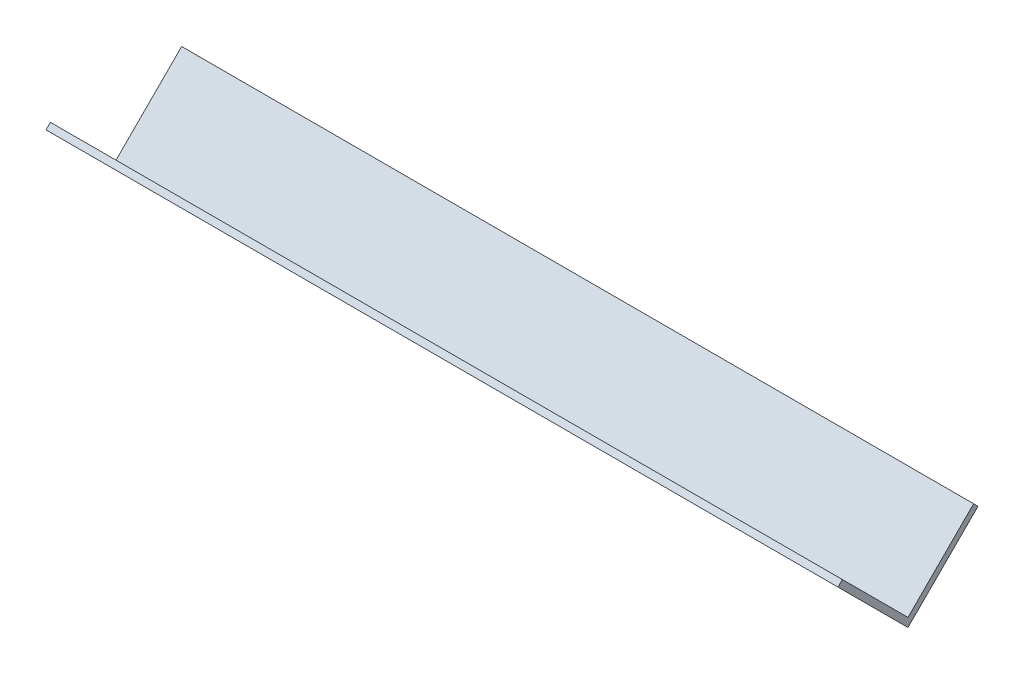
SolidWorks part; units mm, degrees
ref_plane "Front Plane" through (0, 0, 0) normal (0, 0, 1) x (1, 0, 0)
ref_plane "Top Plane" through (0, 0, 0) normal (0, 1, 0) x (1, 0, 0)
ref_plane "Right Plane" through (0, 0, 0) normal (1, 0, 0) x (0, 0, -1)
sketch "Sketch1" plane through (0, 0, 0) normal (1, 0, 0) x (0, 0, -1)
  line L0 (0, 0) -> (-35.921, 35.921)
  line L1 (-35.921, 35.921) -> (-33.676, 38.1661)
  line L2 (-33.676, 38.1661) -> (0, 4.4901)
  line L3 (0, 4.4901) -> (33.676, 38.1661)
  line L4 (33.676, 38.1661) -> (35.921, 35.921)
  line L5 (35.921, 35.921) -> (0, 0)
  dimension "D1" = 50.8
  dimension "D2" = 3.175
extrude "Boss-Extrude1" add sketch "Sketch1" along normal blind 406.4
